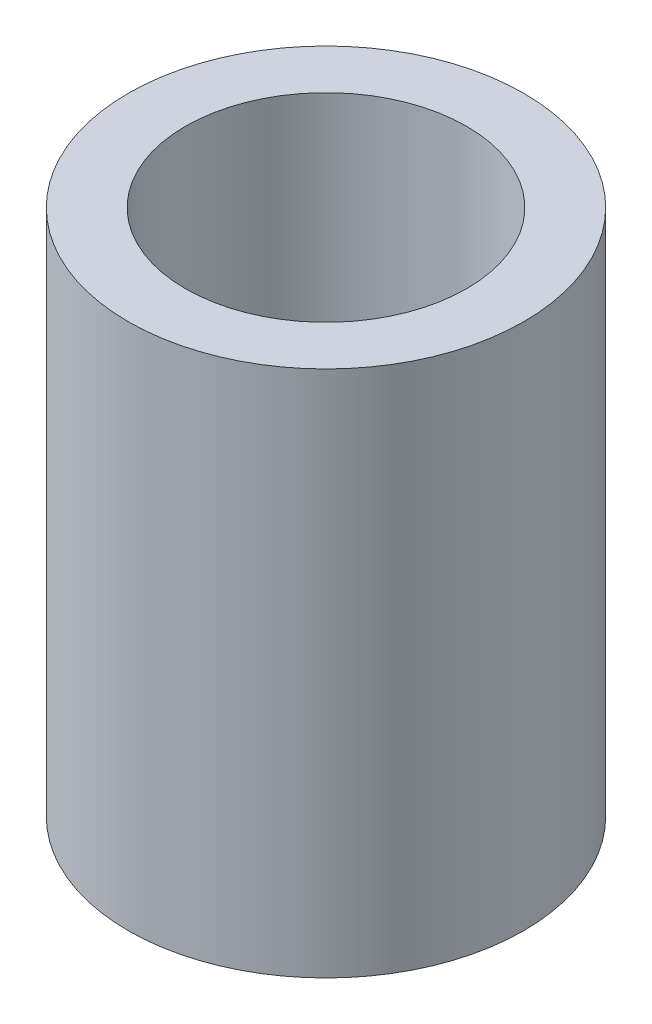
SolidWorks part; units mm, degrees
ref_plane "Front Plane" through (0, 0, 0) normal (0, 0, 1) x (1, 0, 0)
ref_plane "Top Plane" through (0, 0, 0) normal (0, 1, 0) x (1, 0, 0)
ref_plane "Right Plane" through (0, 0, 0) normal (1, 0, 0) x (0, 0, -1)
sketch "Sketch1" plane through (0, 0, 0) normal (0, 1, 0) x (1, 0, 0)
  circle A0 centre (0, 0) radius 2.25
  circle A1 centre (0, 0) radius 1.6
  dimension "D1" = 4.5
  dimension "D2" = 3.2
extrude "Boss-Extrude1" add sketch "Sketch1" along normal blind 6
